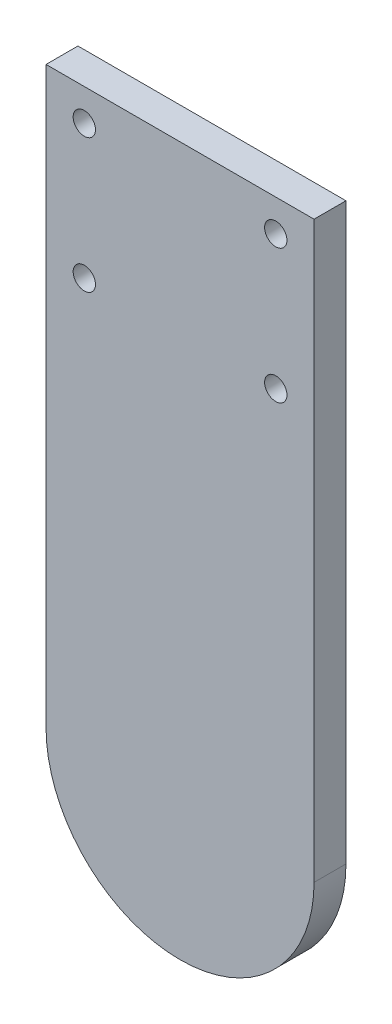
SolidWorks part; units mm, degrees
ref_plane "Front Plane" through (0, 0, 0) normal (0, 0, 1) x (1, 0, 0)
ref_plane "Top Plane" through (0, 0, 0) normal (0, 1, 0) x (1, 0, 0)
ref_plane "Right Plane" through (0, 0, 0) normal (1, 0, 0) x (0, 0, -1)
sketch "Sketch1" plane through (0, 0, 0) normal (0, 0, 1) x (1, 0, 0)
  line L2 (-21, 0) -> (-21, 90)
  line L3 (-21, 90) -> (21, 90)
  line L4 (21, 0) -> (21, 90)
  arc A0 (-21, 0) -> (21, 0) centre (0, 0) ccw
  dimension "D1" = 42
  dimension "D2" = 90
extrude "Boss-Extrude1" add sketch "Sketch1" along normal blind 5
sketch "Sketch2" plane through (0, 0, 0) normal (0, 0, -1) x (-1, 0, 0)
  line L0 (-21, 0) -> (-21, 90) construction
  line L1 (-21, 90) -> (21, 90) construction
  line L2 (0, 102.605) -> (0, 90.4352) construction
  circle A0 centre (-15, 85) radius 1.75
  circle A1 centre (-15, 64) radius 1.75
  circle A2 centre (15, 64) radius 1.75
  circle A3 centre (15, 85) radius 1.75
  dimension "D2" = 3.5
  dimension "D5" = 3.5
  dimension "D1" = 6
  dimension "D3" = 5
  dimension "D4" = 21
  dimension "D6" = 6
extrude "Cut-Extrude1" cut sketch "Sketch2" against normal through all
sketch "Sketch3" plane through (0, 0, 0) normal (0, 0, -1) x (-1, 0, 0)
  circle A0 centre (0, 0) radius 4
  dimension "D1" = 8
extrude "Cut-Extrude2" cut sketch "Sketch3" against normal blind 3
sketch "Sketch4" plane through (0, 0, 0) normal (0, 0, -1) x (-1, 0, 0)
  circle A0 centre (0, 0) radius 6
  circle A1 centre (0, 0) radius 4
  dimension "D1" = 12
extrude "Boss-Extrude2" add sketch "Sketch4" along normal blind 1
